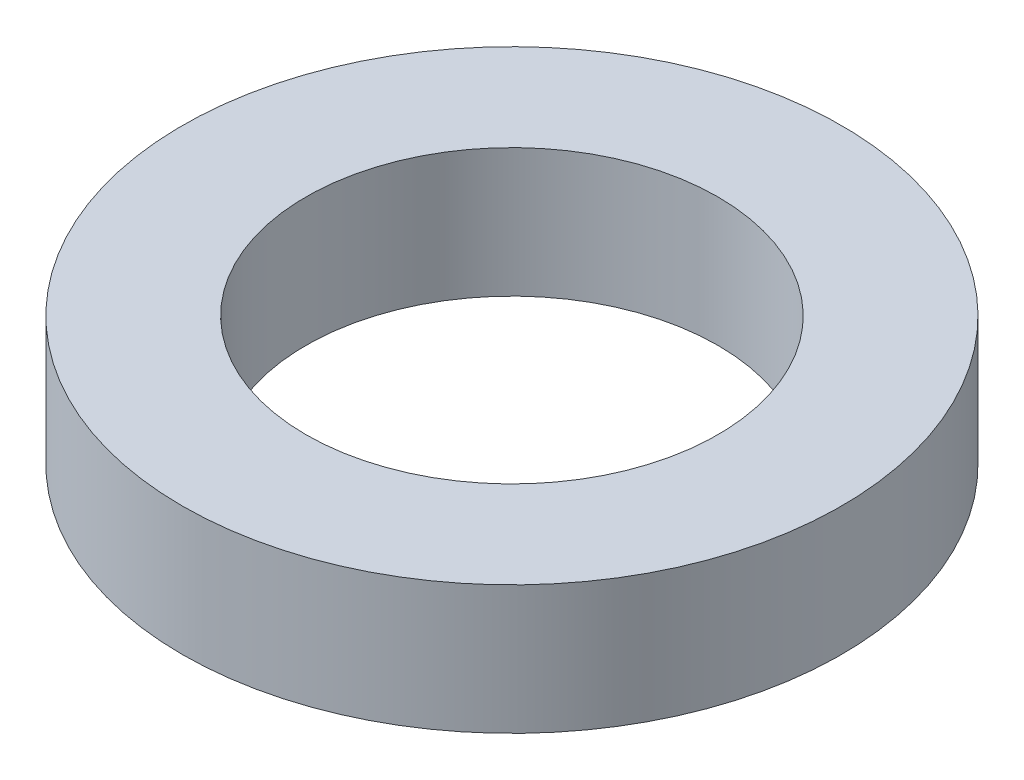
SolidWorks part; units mm, degrees
ref_plane "Front Plane" through (0, 0, 0) normal (0, 0, 1) x (1, 0, 0)
ref_plane "Top Plane" through (0, 0, 0) normal (0, 1, 0) x (1, 0, 0)
ref_plane "Right Plane" through (0, 0, 0) normal (1, 0, 0) x (0, 0, -1)
sketch "Sketch1" plane through (0, 0, 0) normal (0, 1, 0) x (1, 0, 0)
  circle A0 centre (0, 0) radius 12.7
  circle A1 centre (0, 0) radius 7.9375
  dimension "D1" = 15.875
  dimension "D2" = 25.4
extrude "Boss-Extrude1" add sketch "Sketch1" along normal blind 4.9566
